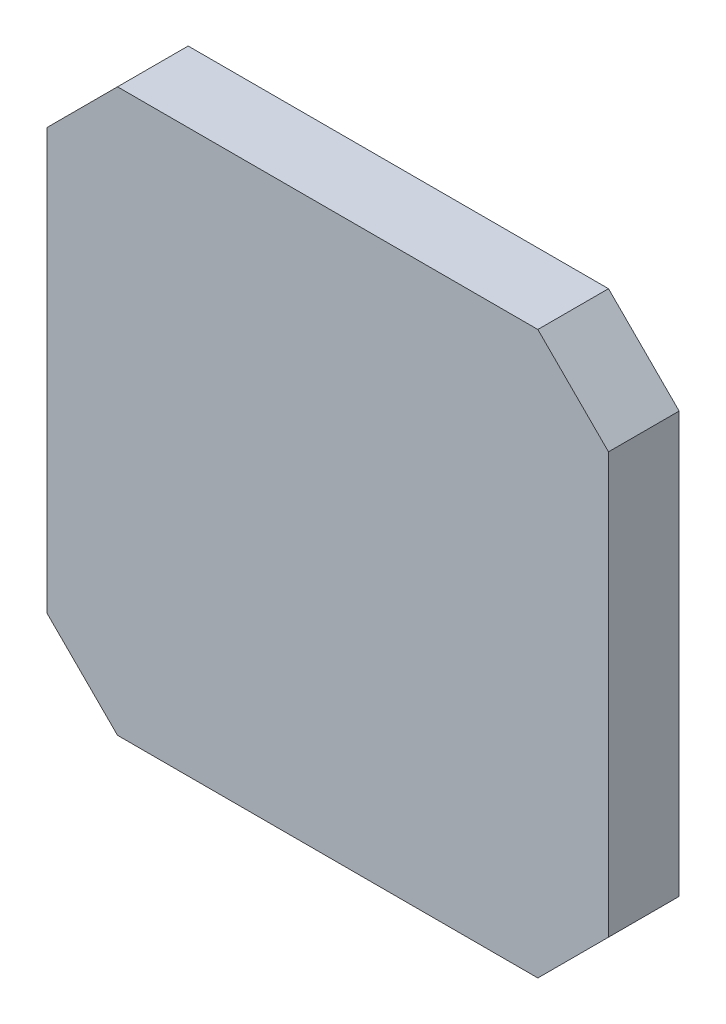
SolidWorks part; units mm, degrees
ref_plane "前视基准面" through (0, 0, 0) normal (0, 0, 1) x (1, 0, 0)
ref_plane "上视基准面" through (0, 0, 0) normal (0, 1, 0) x (1, 0, 0)
ref_plane "右视基准面" through (0, 0, 0) normal (1, 0, 0) x (0, 0, -1)
sketch "草图1" plane through (0, 0, 0) normal (0, 0, 1) x (1, 0, 0)
  line L1 (-79.5, 79.5) -> (79.5, 79.5)
  line L2 (-79.5, 79.5) -> (-79.5, -79.5)
  line L3 (-79.5, -79.5) -> (79.5, -79.5)
  line L4 (79.5, 79.5) -> (79.5, -79.5)
  line L5 (-79.5, 79.5) -> (79.5, -79.5) construction
  line L6 (-79.5, -79.5) -> (79.5, 79.5) construction
  point P0 (0, 0)
  dimension "D1" = 159
  dimension "D2" = 159
extrude "凸台-拉伸1" add sketch "草图1" along normal blind 20
chamfer "倒角1" distance 20 angle 45 4 edges at (79.5, 79.5, 10) (79.5, -79.5, 10) (-79.5, -79.5, 10) (-79.5, 79.5, 10)
